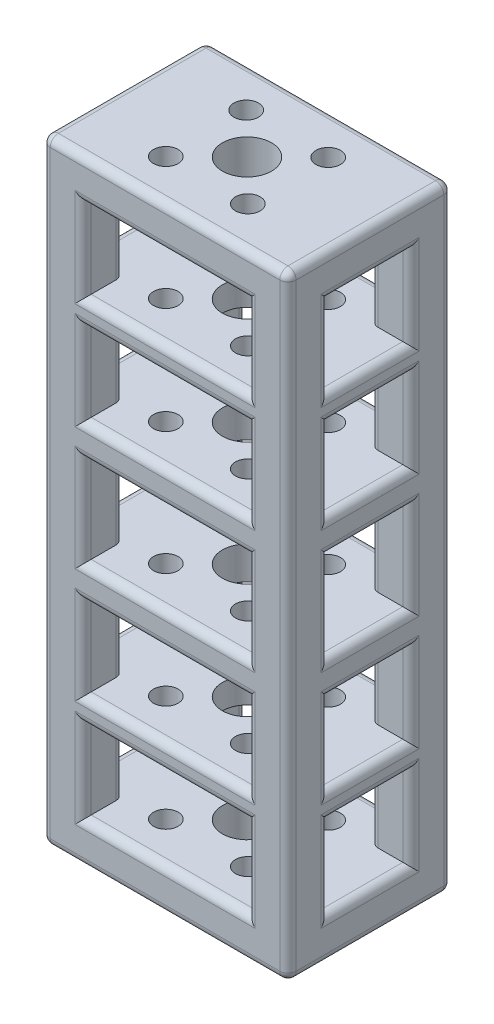
SolidWorks part; units mm, degrees
ref_plane "Płaszczyzna przednia" through (0, 0, 0) normal (0, 0, 1) x (1, 0, 0)
ref_plane "Płaszczyzna górna" through (0, 0, 0) normal (0, 1, 0) x (1, 0, 0)
ref_plane "Płaszczyzna prawa" through (0, 0, 0) normal (1, 0, 0) x (0, 0, -1)
sketch "Szkic1" plane through (0, 0, 0) normal (0, 1, 0) x (1, 0, 0)
  line L1 (0, 0) -> (30, 0)
  line L2 (0, 0) -> (0, 20)
  line L3 (0, 20) -> (30, 20)
  line L4 (30, 0) -> (30, 20)
  circle A0 centre (15, 10) radius 3
  circle A1 centre (10, 14.9) radius 1.5
  circle A2 centre (20, 14.9) radius 1.5
  circle A3 centre (20, 5.1) radius 1.5
  circle A4 centre (10, 5.1) radius 1.5
  dimension "D5" = 6
  dimension "D14" = 3
  dimension "D15" = 3
  dimension "D16" = 3
  dimension "D17" = 3
  dimension "D1" = 20
  dimension "D2" = 30
  dimension "D3" = 15
  dimension "D4" = 10
  dimension "D6" = 5
  dimension "D7" = 5
  dimension "D8" = 5
  dimension "D9" = 5
  dimension "D10" = 4.9
  dimension "D11" = 4.9
  dimension "D12" = 4.9
  dimension "D13" = 4.9
extrude "Dodanie-wyciągnięcie1" add sketch "Szkic1" along normal blind 75
sketch "Szkic2" plane through (30, 0, 0) normal (1, 0, 0) x (0, 0, -1)
  line L0 (0, 75) -> (20, 75) construction
  line L1 (5, 70) -> (15, 70)
  line L2 (5, 70) -> (5, 60)
  line L3 (5, 60) -> (15, 60)
  line L4 (15, 70) -> (15, 60)
  line L5 (20, 75) -> (20, 0) construction
  line L6 (0, 75) -> (0, 0) construction
  line L7 (0, 0) -> (20, 0) construction
  line L8 (5, 57) -> (15, 57)
  line L9 (5, 57) -> (5, 47)
  line L10 (5, 47) -> (15, 47)
  line L11 (15, 57) -> (15, 47)
  line L12 (5, 15) -> (15, 15)
  line L13 (5, 15) -> (5, 5)
  line L14 (5, 5) -> (15, 5)
  line L15 (15, 15) -> (15, 5)
  line L17 (5, 43) -> (15, 43)
  line L18 (5, 43) -> (5, 32)
  line L19 (5, 32) -> (15, 32)
  line L20 (15, 43) -> (15, 32)
  line L21 (5, 28) -> (15, 28)
  line L22 (5, 28) -> (5, 18)
  line L23 (5, 18) -> (15, 18)
  line L24 (15, 28) -> (15, 18)
  point P21 (0, 37.5)
  dimension "D1" = 5
  dimension "D2" = 5
  dimension "D3" = 5
  dimension "D4" = 10
  dimension "D5" = 5
  dimension "D6" = 5
  dimension "D7" = 5
  dimension "D8" = 10
  dimension "D9" = 5
  dimension "D10" = 5
  dimension "D11" = 10
  dimension "D12" = 3
  dimension "D13" = 5
  dimension "D14" = 5
  dimension "D15" = 4
  dimension "D16" = 11
  dimension "D17" = 5
  dimension "D18" = 5
  dimension "D19" = 10
  dimension "D20" = 3
  dimension "D21" = 4
extrude "Wytnij-wyciągnięcie1" cut sketch "Szkic2" against normal blind 79 and the other way blind 60
sketch "Szkic3" plane through (0, 0, 0) normal (0, 0, 1) x (1, 0, 0)
  line L0 (0, 75) -> (30, 75) construction
  line L1 (5, 70) -> (25, 70)
  line L2 (5, 70) -> (5, 60)
  line L3 (5, 60) -> (25, 60)
  line L4 (25, 70) -> (25, 60)
  line L5 (30, 75) -> (30, 0) construction
  line L6 (0, 75) -> (0, 0) construction
  line L8 (0, 0) -> (30, 0) construction
  line L9 (5, 57) -> (25, 57)
  line L10 (5, 57) -> (5, 47)
  line L11 (5, 47) -> (25, 47)
  line L12 (25, 57) -> (25, 47)
  line L13 (5, 15) -> (25, 15)
  line L14 (5, 15) -> (5, 5)
  line L15 (5, 5) -> (25, 5)
  line L16 (25, 15) -> (25, 5)
  line L18 (5, 43) -> (25, 43)
  line L19 (5, 43) -> (5, 32)
  line L20 (5, 32) -> (25, 32)
  line L21 (25, 43) -> (25, 32)
  line L22 (5, 28) -> (25, 28)
  line L23 (5, 28) -> (5, 18)
  line L24 (5, 18) -> (25, 18)
  line L25 (25, 28) -> (25, 18)
  point P28 (5, 23)
  dimension "D1" = 5
  dimension "D2" = 5
  dimension "D3" = 5
  dimension "D4" = 10
  dimension "D5" = 5
  dimension "D6" = 5
  dimension "D7" = 5
  dimension "D8" = 10
  dimension "D9" = 5
  dimension "D10" = 5
  dimension "D11" = 10
  dimension "D12" = 3
  dimension "D13" = 3
  dimension "D14" = 10
  dimension "D15" = 4
  dimension "D16" = 11
  dimension "D17" = 4
  dimension "D18" = 5
  dimension "D19" = 5
  dimension "D20" = 5
  dimension "D21" = 5
extrude "Wytnij-wyciągnięcie3" cut sketch "Szkic3" against normal blind 260
fillet "Zaokrąglenie12" radius 1 92 edges at (30, 60, -10) (30, 65, -15) (30, 70, -10) (30, 65, -5) (30, 32, -10) (30, 37.5, -15) (30, 43, -10) (30, 37.5, -5) (30, 47, -10) (30, 52, -15) (30, 57, -10) (30, 52, -5) (30, 75, -10) (30, 0, -10) (30, 5, -10) (30, 10, -15) (30, 15, -10) (30, 10, -5) (30, 18, -10) (30, 23, -15) (30, 28, -10) (30, 23, -5) (30, 37.5, -20) (15, 75, -20) (15, 0, -20) (25, 52, -20) (15, 47, -20) (5, 52, -20) (15, 57, -20) (25, 10, -20) (15, 5, -20) (5, 10, -20) (15, 15, -20) (25, 37.5, -20) (15, 32, -20) (5, 37.5, -20) (15, 43, -20) (25, 23, -20) (15, 18, -20) (5, 23, -20) (15, 28, -20) (25, 65, -20) (15, 60, -20) (5, 65, -20) (15, 70, -20) (0, 70, -10) (0, 65, -15) (0, 60, -10) (0, 65, -5) (0, 43, -10) (0, 37.5, -15) (0, 32, -10) (0, 37.5, -5) (0, 57, -10) (0, 52, -15) (0, 47, -10) (0, 52, -5) (0, 37.5, -20) (0, 75, -10) (0, 0, -10) (0, 15, -10) (0, 10, -15) (0, 5, -10) (0, 10, -5) (0, 28, -10) (0, 23, -15) (0, 18, -10) (0, 23, -5) (0, 37.5, 0) (15, 75, 0) (30, 37.5, 0) (15, 0, 0) (25, 52, 0) (15, 57, 0) (5, 52, 0) (15, 47, 0) (25, 10, 0) (15, 15, 0) (5, 10, 0) (15, 5, 0) (25, 37.5, 0) (15, 43, 0) (5, 37.5, 0) (15, 32, 0) (25, 23, 0) (15, 28, 0) (5, 23, 0) (15, 18, 0) (25, 65, 0) (15, 70, 0) (5, 65, 0) (15, 60, 0)
fillet "Zaokrąglenie13" radius 1 20 edges at (5, 52, -5) (5, 65, -5) (5, 65, -15) (5, 52, -15) (5, 37.5, -15) (5, 37.5, -5) (5, 23, -5) (5, 23, -15) (5, 10, -15) (5, 10, -5) (25, 10, -15) (25, 10, -5) (25, 23, -5) (25, 23, -15) (25, 37.5, -15) (25, 37.5, -5) (25, 52, -5) (25, 65, -5) (25, 52, -15) (25, 65, -15)
